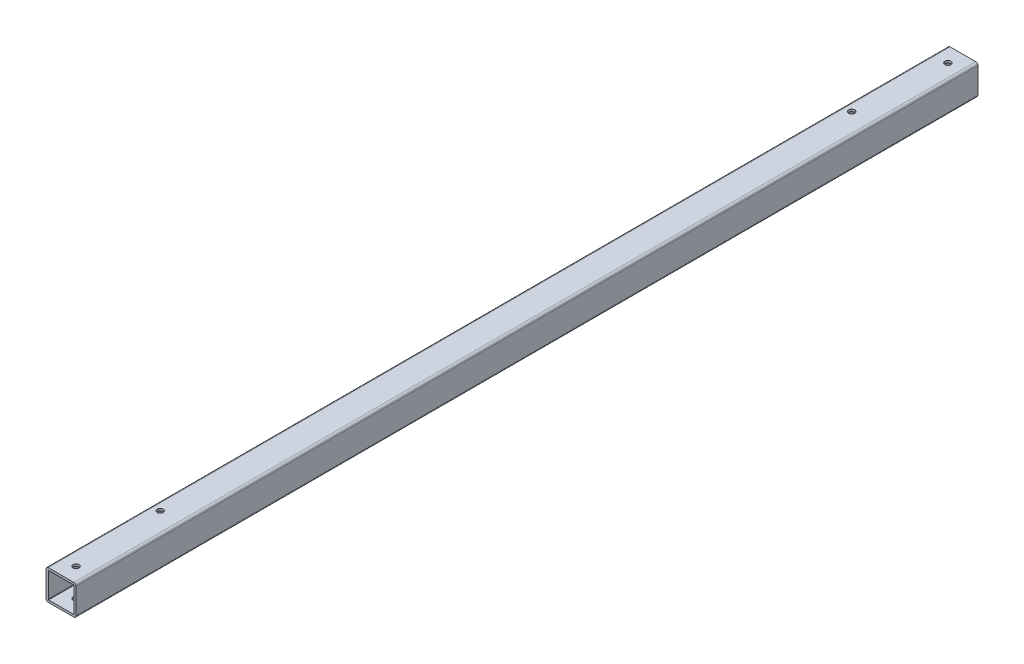
SolidWorks part; units mm, degrees
ref_plane "Front Plane" through (0, 0, 0) normal (0, 0, 1) x (1, 0, 0)
ref_plane "Top Plane" through (0, 0, 0) normal (0, 1, 0) x (1, 0, 0)
ref_plane "Right Plane" through (0, 0, 0) normal (1, 0, 0) x (0, 0, -1)
sketch "Sketch1" plane through (0, 0, 0) normal (0, 0, 1) x (1, 0, 0)
  line L1 (-20, 20) -> (20, 20)
  line L2 (-20, 20) -> (-20, -20)
  line L3 (-20, -20) -> (20, -20)
  line L4 (20, 20) -> (20, -20)
  line L5 (-20, 20) -> (20, -20) construction
  line L6 (-20, -20) -> (20, 20) construction
  point P0 (0, 0)
  dimension "D1" = 40
  dimension "D2" = 40
extrude "Extrude-Thin1" add sketch "Sketch1" along normal blind 1200 thin
fillet "Fillet1" radius 0.5 4 edges at (-17, -17, 600) (-17, 17, 600) (17, 17, 600) (17, -17, 600)
fillet "Fillet2" radius 3 4 edges at (20, -20, 600) (-20, -20, 600) (20, 20, 600) (-20, 20, 600)
hole_wizard "Ø8.0 (8) Diameter Hole1" positions "Sketch4" profile "Sketch3" hole size "Ø8.0" standard "ANSI Metric" end condition through all
sketch "Sketch4" plane through (0, 20, 0) normal (0, 1, 0) x (1, 0, 0)
  line L2 (0, 0) -> (0, -1200) construction
  line L3 (17, -1200) -> (-17, -1200) construction
  line L5 (17, 0) -> (-17, 0) construction
  point P0 (0, -20)
  point P2 (0, -1180)
  dimension "D1" = 20
  dimension "D2" = 20
sketch "Sketch3" plane through (0, 20, 20) normal (1, 0, 0) x (0, 0, 1)
  line L0 (0, 0) -> (0, 40)
  line L1 (0, 40) -> (4, 40)
  line L2 (4, 40) -> (4, 0)
  line L5 (4, 0) -> (0, 0)
  line L11 (0, -6.35) -> (0, 107.95) construction
  dimension "Thru Hole Dia." = 8
  dimension "Thru Hole Depth" = 40
hole_wizard "Ø8.0 (8) Diameter Hole2" positions "Sketch6" profile "Sketch5" hole size "Ø8.0" standard "ANSI Metric" end condition through all
sketch "Sketch6" plane through (0, 20, 0) normal (0, 1, 0) x (1, 0, 0)
  line L0 (20, 0) -> (20, -1200) construction
  circle A0 centre (0, -20) radius 4 construction
  circle A1 centre (0, -1180) radius 4 construction
  point P0 (-8, -1060)
  point P2 (-8, -140)
  dimension "D1" = 120
  dimension "D4" = 28
  dimension "D2" = 28
  dimension "D3" = 120
sketch "Sketch5" plane through (-8, 20, 1060) normal (1, 0, 0) x (0, 0, 1)
  line L0 (0, 0) -> (0, 40)
  line L1 (0, 40) -> (4, 40)
  line L2 (4, 40) -> (4, 0)
  line L5 (4, 0) -> (0, 0)
  line L11 (0, -6.35) -> (0, 107.95) construction
  dimension "Thru Hole Dia." = 8
  dimension "Thru Hole Depth" = 40
equation "\"a\"= \"Beam Profile@Plasma Beta.Assembly\""
equation "\"b\"= 3"
equation "\"L\"= \"Width@Plasma Beta.Assembly\""
equation "\"D2@Sketch1\"=\"a\""
equation "\"D1@Sketch1\"=\"a\""
equation "\"D1@Extrude-Thin1\"=\"L\""
equation "\"D5@Extrude-Thin1\"=\"b\""
equation "\"D1@Fillet2\"=\"b\""
